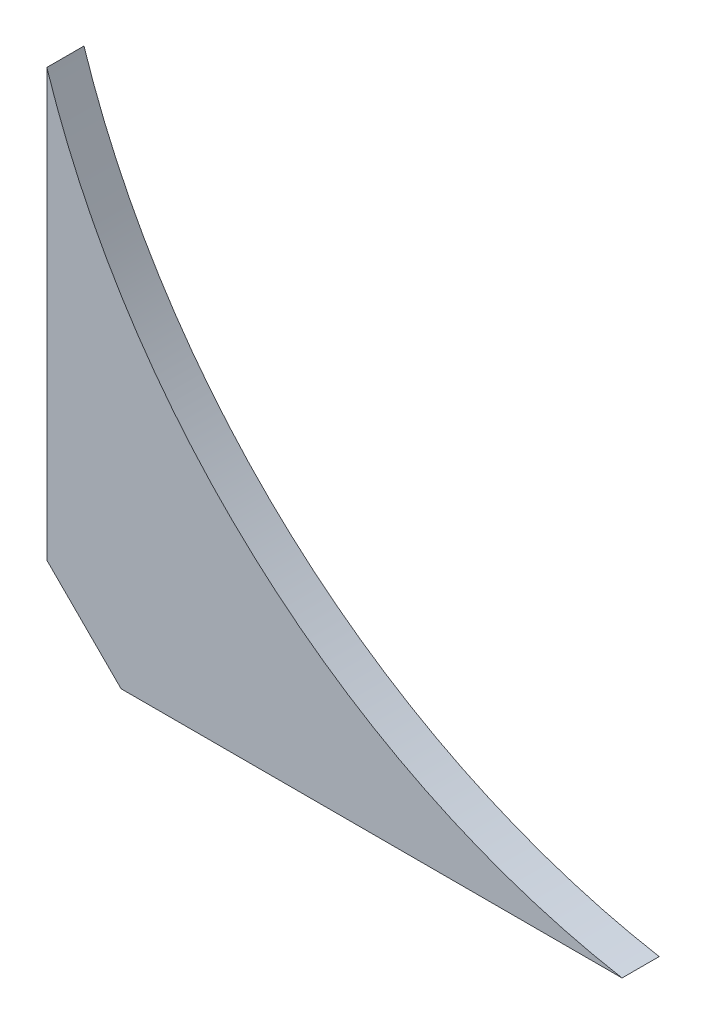
SolidWorks part; units mm, degrees
material "Plain Carbon Steel"
ref_plane "Front Plane" through (0, 0, 0) normal (0, 0, 1) x (1, 0, 0)
ref_plane "Top Plane" through (0, 0, 0) normal (0, 1, 0) x (1, 0, 0)
ref_plane "Right Plane" through (0, 0, 0) normal (1, 0, 0) x (0, 0, -1)
sketch "Sketch1" plane through (0, 0, 0) normal (0, 0, 1) x (1, 0, 0)
  line L0 (-50.1632, 92.915) -> (-50.1632, -22.085)
  line L1 (-30.1632, -42.085) -> (104.8368, -42.085)
  line L2 (-50.1632, -22.085) -> (-30.1632, -42.085)
  arc A0 (-50.1632, 92.915) -> (104.8368, -42.085) centre (140.023, 154.7955) ccw
  point P1 (-50.1632, -42.085)
  dimension "D1" = 200
  dimension "D2" = 135
  dimension "D3" = 135
extrude "Boss-Extrude1" add sketch "Sketch1" along normal mid plane 10
